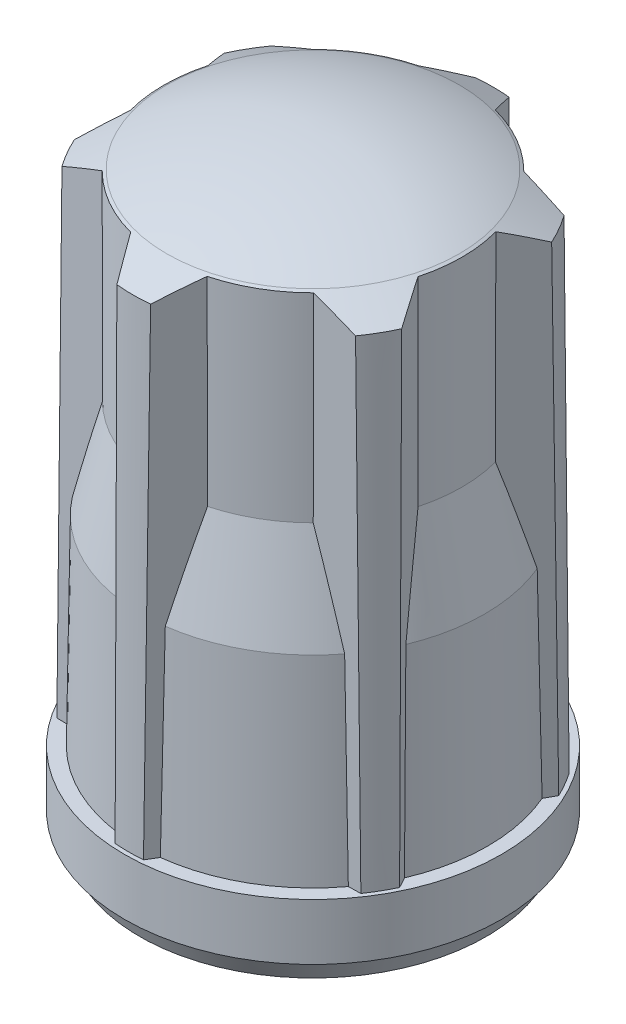
SolidWorks part; units mm, degrees
material "PP Copolímero"
ref_plane "Plano frontal" through (0, 0, 0) normal (0, 0, 1) x (1, 0, 0)
ref_plane "Plano superior" through (0, 0, 0) normal (0, 1, 0) x (1, 0, 0)
ref_plane "Plano direito" through (0, 0, 0) normal (1, 0, 0) x (0, 0, -1)
sketch "Esboço1" plane through (0, 0, 0) normal (0, 0, 1) x (1, 0, 0)
  line L0 (0, 0) -> (0, 10.75) construction
  line L1 (0, 0) -> (-3.35, 0)
  line L2 (-3.35, 0) -> (-3.35, 1.3)
  line L3 (-3.35, 1.3) -> (-3.1, 1.3)
  line L4 (-2.646, 6.6) -> (-2.65, 10.75)
  line L5 (-3.1, 1.3) -> (-3.05, 4.85)
  line L6 (-3.05, 4.85) -> (-2.646, 6.6)
  line L7 (0, 10.75) -> (0, 0)
  line L8 (0, 10.75) -> (-2.65, 10.75)
  dimension "D1" = 6.7
  dimension "D2" = 10.75
  dimension "D3" = 1.3
  dimension "D4" = 6.1
  dimension "D5" = 3.55
  dimension "D6" = 13
  dimension "D7" = 5.3
  dimension "D8" = 5.3
  dimension "D11" = 6.2
revolve "Revolução1" add sketch "Esboço1" angle 360 about L0
ref_plane "Plano1" through (0, 10, 0) normal (0, -1, 0) x (1, 0, 0)
sketch "Esboço2" plane through (0, 1.3, 0) normal (0, -1, 0) x (1, 0, 0)
  line L0 (0, 2.65) -> (0, -3.1) construction
  line L1 (-0.8376, -2.3) -> (-0.2042, -3.3438)
  line L2 (0.2042, -3.3438) -> (0.8376, -2.3)
  line L3 (-2.65, 0) -> (2.646, 0) construction
  line L4 (0, 0) -> (2.6847, 1.55) construction
  line L5 (0, 0) -> (-3.4103, 1.9689) construction
  line L6 (0.2042, -3.3438) -> (3.0603, 1.3627) construction
  line L7 (-0.2042, -3.3438) -> (-3.0603, 1.3627) construction
  line L8 (-0.3, -3.1859) -> (0.3, -3.1859) construction
  line L9 (2.7103, 1.9689) -> (-2.7103, 1.9689) construction
  line L11 (-0.8376, -2.3) -> (0.8376, -2.3)
  circle A0 centre (0, 0) radius 2.646 construction
  circle A1 centre (0, 0) radius 3.35 construction
  circle A2 centre (0, 0) radius 3.1 construction
  arc A3 (-0.2042, -3.3438) -> (0.2042, -3.3438) centre (0, 0) ccw
  circle A4 centre (0, 0) radius 3.35 construction
  circle A5 centre (0, 0) radius 2.65 construction
  circle A6 centre (0, 0) radius 3.35 construction
  circle A8 centre (0, 0) radius 3.2 construction
  point P12 (0, 0)
  dimension "D10" = 6.7
  dimension "D9" = 2.3
  dimension "D11" = 6.4
  dimension "D1" = 120
  dimension "D2" = 120
  dimension "D3" = 0.2042
  dimension "D4" = 0.6
  dimension "D5" = 0.35
  dimension "D6" = 0.35
  dimension "D7" = 0.7
  dimension "D8" = 0.7
extrude "Extrusão1" add sketch "Esboço2" against normal up to surface (9.45 mm away) up to face at (0, 10.75, -2.65)
pattern_circular "CirPattern1" count 6 over 360 about axis through (0, 0, 0) along (0, 1, 0) of "Extrusão1"
sketch "Esboço3" plane through (0, 0, 0) normal (0, 0, 1) x (1, 0, 0)
  line L0 (-3.2, 9.8377) -> (-2.6, 10.1703)
  line L1 (0, 10.75) -> (0, 11.25)
  line L2 (-3.35, 0) -> (3.35, 0) construction
  line L5 (0, 0) -> (0, 11.25) construction
  line L7 (0, 11.25) -> (-4, 11.25)
  line L8 (-2.9979, 1.3) -> (-3.35, 1.3) construction
  line L9 (-3.2, 9.8377) -> (-3.2745, 1.3)
  line L10 (0.2042, 10.75) -> (-0.2042, 10.75) construction
  line L13 (-4, 11.25) -> (-4, 1.3)
  line L14 (-4, 1.3) -> (-3.2745, 1.3)
  arc A0 (-2.6, 10.1703) -> (0, 10.75) centre (0, 4.63) cw
  dimension "D4" = 0.5
  dimension "D1" = 61
  dimension "D3" = 6.12
  dimension "D2" = 5.2
  dimension "D5" = 8
  dimension "D6" = 6.549
  dimension "D7" = 0.5
  dimension "D8" = 6.4
revolve "Corte-Revolução5" cut sketch "Esboço3" angle 360 about L5
fillet "Filete1" radius 0.3 1 edges at (0, 0, -3.35)
sketch "Esboço24" plane through (0, 0, 0) normal (0, -1, 0) x (1, 0, 0)
  circle A0 centre (0, 0) radius 3.35
  circle A1 centre (0, 0) radius 3.35 construction
extrude "Corte-extrusão1" cut sketch "Esboço24" against normal blind 0.3
sketch "Esboço22" plane through (0, 0, 0) normal (0, 0, 1) x (1, 0, 0)
  line L0 (0, 0) -> (0, 9.4264) construction
  line L1 (-0.5, 0.3) -> (-0.5, -0.1)
  line L3 (-0.5, -0.1) -> (-3.0799, -0.1)
  line L4 (-3.0799, -0.1) -> (-3.275, 0.3)
  line L5 (-3.275, 0.3) -> (0, 0.3) construction
  line L6 (-3.275, 0.3) -> (-0.5, 0.3)
  line L7 (-3.35, 0.3) -> (3.35, 0.3) construction
  dimension "D1" = 0.4
  dimension "D2" = 6.55
  dimension "D3" = 26
  dimension "D4" = 6.55
  dimension "D5" = 0.5
revolve "Revolução3" add sketch "Esboço22" angle 360 about L0
sketch "Esboço8" plane through (0, 0, 0) normal (0, 0, 1) x (1, 0, 0)
  line L0 (0, -0.1) -> (0, 10.75) construction
  line L3 (-2.05, 9.07) -> (-2.05, 8.47)
  line L6 (-2.8083, -0.1) -> (0, -0.1)
  line L7 (-0.5, -0.1) -> (0.5, -0.1) construction
  line L14 (-2.65, 0.25) -> (-2.79, 0.25)
  line L15 (-2.05, 7.37) -> (-2.05, 7.87)
  line L16 (-2.05, 7.37) -> (-2.45, 5.6374)
  line L17 (-2.45, 5.6374) -> (-2.45, 0.45)
  line L18 (-2.79, 0.25) -> (-2.8083, -0.1)
  line L20 (-2.8083, -0.1) -> (0, -0.1)
  arc A0 (-2.45, 0.45) -> (-2.65, 0.25) centre (-2.65, 0.45) cw
  arc A2 (0, 9.45) -> (-2.05, 9.07) centre (0.0741, 3.3304) ccw
  arc A4 (-2.05, 8.47) -> (-2.05, 7.87) centre (-2.275, 8.17) cw
  point P10 (-2.45, 0.25)
  point P28 (-1.9, 8.17)
  dimension "D4" = 6.12
  dimension "D24" = 0.98
  dimension "D26" = 5.58
  dimension "D20" = 0.15
  dimension "D23" = 2.45
  dimension "D3" = 0.2
  dimension "D2" = 4.1
  dimension "D14" = 0.6
  dimension "D15" = 0.6
  dimension "D19" = 1.3
  dimension "D21" = 0.5
  dimension "D22" = 13
  dimension "D25" = 9.2
  dimension "D27" = 3
revolve "Corte-Revolução6" cut sketch "Esboço8" angle 360 about L0
